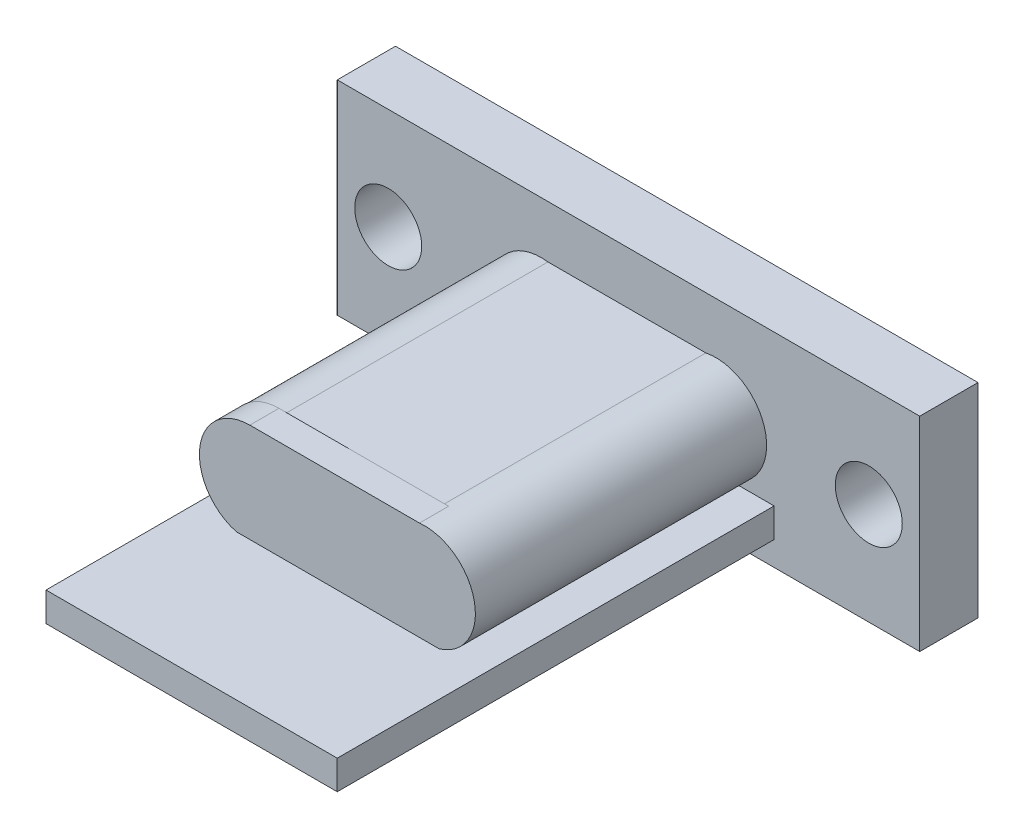
SolidWorks part; units mm, degrees
ref_plane "Front Plane" through (0, 0, 0) normal (0, 0, 1) x (1, 0, 0)
ref_plane "Top Plane" through (0, 0, 0) normal (0, 1, 0) x (1, 0, 0)
ref_plane "Right Plane" through (0, 0, 0) normal (1, 0, 0) x (0, 0, -1)
sketch "Sketch1" plane through (0, 0, 0) normal (0, 0, 1) x (1, 0, 0)
  line L0 (0, 3.5) -> (1.75, 3.5) construction
  line L1 (0, 0) -> (20, 0)
  line L2 (0, 0) -> (0, 7)
  line L3 (0, 7) -> (20, 7)
  line L4 (20, 0) -> (20, 7)
  line L5 (7, 3.5) -> (13, 3.5) construction
  line L6 (7, 4.75) -> (13, 4.75)
  line L7 (7, 2.25) -> (13, 2.25)
  line L8 (18.25, 3.5) -> (20, 3.5) construction
  line L9 (10, 7) -> (10, 0) construction
  circle A0 centre (1.75, 3.5) radius 1.15
  circle A1 centre (18.25, 3.5) radius 1.15
  arc A2 (7, 4.75) -> (7, 2.25) centre (7, 3.5) ccw
  arc A3 (13, 2.25) -> (13, 4.75) centre (13, 3.5) ccw
  point P11 (10, 3.5)
  point P18 (5.75, 3.5)
  point P19 (14.25, 3.5)
  point P22 (10, 3.5)
  point P23 (10, 3.5)
  point P24 (9.7955, 3.5)
  dimension "D3" = 2.3
  dimension "D4" = 2.3
  dimension "D5" = 16.5
  dimension "D8" = 2.5
  dimension "D1" = 20
  dimension "D2" = 7
  dimension "D7" = 8.5
extrude "Boss-Extrude1" add sketch "Sketch1" along normal blind 2
sketch "Sketch6" plane through (0, 0, 2) normal (0, 0, 1) x (1, 0, 0)
  line L0 (7, 3.5) -> (13, 3.5) construction
  line L1 (7.2331, 5.202) -> (12.6547, 5.2075)
  line L3 (7, 3.5) -> (13, 3.5) construction
  line L4 (7, 4.77) -> (13, 4.77)
  line L5 (7, 2.23) -> (13, 2.23)
  line L6 (0, 0) -> (20, 0) construction
  line L7 (5, 1.8308) -> (6.5938, 1.8308)
  line L8 (5, 1.8308) -> (5, 0.8308)
  line L9 (5, 0.8308) -> (15, 0.8308)
  line L10 (15, 1.8308) -> (15, 0.8308)
  line L11 (13.4986, 1.8308) -> (15, 1.8308)
  arc A0 (7.2331, 5.202) -> (6.5938, 1.8308) centre (7, 3.5) ccw
  arc A1 (13.4986, 1.8308) -> (12.6547, 5.2075) centre (13, 3.5) ccw
  arc A2 (7, 4.77) -> (7, 2.23) centre (7, 3.5) ccw
  arc A3 (13, 2.23) -> (13, 4.77) centre (13, 3.5) ccw
  point P4 (9.95, 3.3)
  point P11 (10, 3.5)
  point P22 (10, 0)
  point P23 (10, 0.8308)
  dimension "D1" = 2.54
  dimension "D2" = 10
  dimension "D3" = 1
extrude "Boss-Extrude11" add sketch "Sketch6" along normal blind 10
sketch "Sketch7" plane through (0, 0, 12) normal (0, 0, 1) x (1, 0, 0)
  line L0 (7, 3.5) -> (13, 3.5) construction
  line L1 (7, 5.2331) -> (13, 5.2331)
  line L2 (7, 1.7669) -> (13, 1.7669)
  arc A0 (7, 5.2331) -> (7, 1.7669) centre (7, 3.5) ccw
  arc A1 (13, 1.7669) -> (13, 5.2331) centre (13, 3.5) ccw
  point P4 (10, 3.5)
extrude "Boss-Extrude12" add sketch "Sketch7" against normal blind 1
sketch "Sketch8" plane through (0, 0, 12) normal (0, 0, 1) x (1, 0, 0)
  line L1 (5, 1.8308) -> (15, 1.8308)
  line L2 (5, 1.8308) -> (5, 0.8308)
  line L3 (5, 0.8308) -> (15, 0.8308)
  line L4 (15, 1.8308) -> (15, 0.8308)
extrude "Boss-Extrude13" add sketch "Sketch8" along normal blind 5
